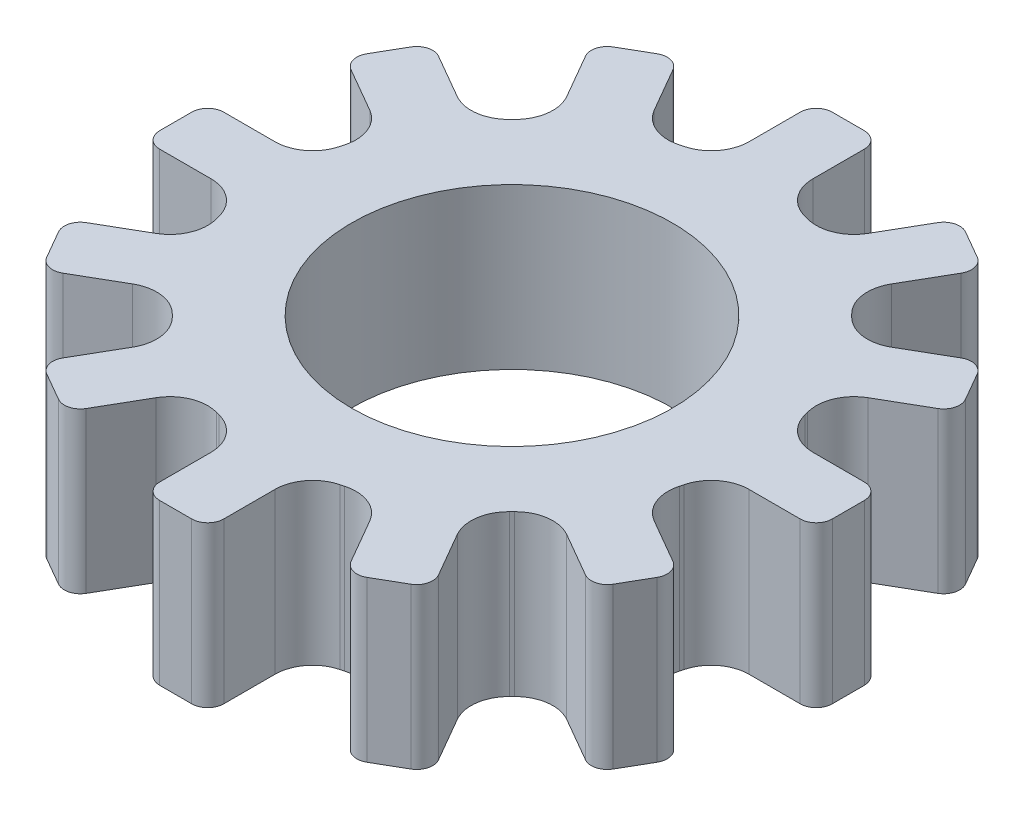
SolidWorks part; units mm, degrees
material "6061 Alloy"
ref_plane "Front Plane" through (0, 0, 0) normal (0, 0, 1) x (1, 0, 0)
ref_plane "Top Plane" through (0, 0, 0) normal (0, 1, 0) x (1, 0, 0)
ref_plane "Right Plane" through (0, 0, 0) normal (1, 0, 0) x (0, 0, -1)
sketch "Sketch1" plane through (0, 0, 0) normal (0, 1, 0) x (1, 0, 0)
  line L0 (0, 0) -> (0, 9.525) construction
  line L7 (-1.27, 10.6703) -> (-1.27, 12.7)
  line L8 (-0.635, 13.335) -> (0.635, 13.335)
  line L9 (1.27, 12.7) -> (1.27, 10.6703)
  line L10 (4.2353, 9.8757) -> (5.2501, 11.6335)
  line L11 (6.1176, 11.8659) -> (7.2174, 11.2309)
  line L12 (7.4499, 10.3635) -> (6.435, 8.6057)
  line L13 (8.6057, 6.435) -> (10.3635, 7.4499)
  line L14 (11.2309, 7.2174) -> (11.8659, 6.1176)
  line L15 (11.6335, 5.2501) -> (9.8757, 4.2353)
  line L16 (10.6703, 1.27) -> (12.7, 1.27)
  line L17 (13.335, 0.635) -> (13.335, -0.635)
  line L18 (12.7, -1.27) -> (10.6703, -1.27)
  line L19 (9.8757, -4.2353) -> (11.6335, -5.2501)
  line L20 (11.8659, -6.1176) -> (11.2309, -7.2174)
  line L21 (10.3635, -7.4499) -> (8.6057, -6.435)
  line L22 (6.435, -8.6057) -> (7.4499, -10.3635)
  line L23 (7.2174, -11.2309) -> (6.1176, -11.8659)
  line L24 (5.2501, -11.6335) -> (4.2353, -9.8757)
  line L25 (1.27, -10.6703) -> (1.27, -12.7)
  line L26 (0.635, -13.335) -> (-0.635, -13.335)
  line L27 (-1.27, -12.7) -> (-1.27, -10.6703)
  line L28 (-4.2353, -9.8757) -> (-5.2501, -11.6335)
  line L29 (-6.1176, -11.8659) -> (-7.2174, -11.2309)
  line L30 (-7.4499, -10.3635) -> (-6.435, -8.6057)
  line L31 (-8.6057, -6.435) -> (-10.3635, -7.4499)
  line L32 (-11.2309, -7.2174) -> (-11.8659, -6.1176)
  line L33 (-11.6335, -5.2501) -> (-9.8757, -4.2353)
  line L34 (-10.6703, -1.27) -> (-12.7, -1.27)
  line L35 (-13.335, -0.635) -> (-13.335, 0.635)
  line L36 (-12.7, 1.27) -> (-10.6703, 1.27)
  line L37 (-9.8757, 4.2353) -> (-11.6335, 5.2501)
  line L38 (-11.8659, 6.1176) -> (-11.2309, 7.2174)
  line L39 (-10.3635, 7.4499) -> (-8.6057, 6.435)
  line L40 (-6.435, 8.6057) -> (-7.4499, 10.3635)
  line L41 (-7.2174, 11.2309) -> (-6.1176, 11.8659)
  line L42 (-5.2501, 11.6335) -> (-4.2353, 9.8757)
  line L43 (0, 0) -> (2.3922, 9.2197) construction
  line L44 (-2.3922, 9.2197) -> (-2.5381, 9.1806)
  line L45 (2.5381, 9.1806) -> (2.3922, 9.2197)
  line L46 (6.7884, 6.6816) -> (6.6816, 6.7884)
  line L47 (9.2197, 2.3922) -> (9.1806, 2.5381)
  line L48 (9.1806, -2.5381) -> (9.2197, -2.3922)
  line L49 (6.6816, -6.7884) -> (6.7884, -6.6816)
  line L50 (2.3922, -9.2197) -> (2.5381, -9.1806)
  line L51 (-2.5381, -9.1806) -> (-2.3922, -9.2197)
  line L52 (-6.7884, -6.6816) -> (-6.6816, -6.7884)
  line L53 (-9.2197, -2.3922) -> (-9.1806, -2.5381)
  line L54 (-9.1806, 2.5381) -> (-9.2197, 2.3922)
  line L55 (-6.6816, 6.7884) -> (-6.7884, 6.6816)
  line L56 (0, 0) -> (-2.5381, 9.1806) construction
  circle A0 centre (0, 0) radius 6.3627
  circle A1 centre (0, 0) radius 9.525 construction
  arc A2 (-2.3922, 9.2197) -> (-1.27, 10.6703) centre (-2.7686, 10.6703) ccw
  arc A3 (0.635, 13.335) -> (1.27, 12.7) centre (0.635, 12.7) cw
  arc A4 (1.27, 10.6703) -> (2.3922, 9.2197) centre (2.7686, 10.6703) ccw
  arc A5 (-1.27, 12.7) -> (-0.635, 13.335) centre (-0.635, 12.7) cw
  arc A6 (2.5381, 9.1806) -> (4.2353, 9.8757) centre (2.9375, 10.625) ccw
  arc A7 (7.2174, 11.2309) -> (7.4499, 10.3635) centre (6.8999, 10.681) cw
  arc A8 (6.435, 8.6057) -> (6.6816, 6.7884) centre (7.7328, 7.8564) ccw
  arc A9 (5.2501, 11.6335) -> (6.1176, 11.8659) centre (5.8001, 11.316) cw
  arc A10 (6.7884, 6.6816) -> (8.6057, 6.435) centre (7.8564, 7.7328) ccw
  arc A11 (11.8659, 6.1176) -> (11.6335, 5.2501) centre (11.316, 5.8001) cw
  arc A12 (9.8757, 4.2353) -> (9.1806, 2.5381) centre (10.625, 2.9375) ccw
  arc A13 (10.3635, 7.4499) -> (11.2309, 7.2174) centre (10.681, 6.8999) cw
  arc A14 (9.2197, 2.3922) -> (10.6703, 1.27) centre (10.6703, 2.7686) ccw
  arc A15 (13.335, -0.635) -> (12.7, -1.27) centre (12.7, -0.635) cw
  arc A16 (10.6703, -1.27) -> (9.2197, -2.3922) centre (10.6703, -2.7686) ccw
  arc A17 (12.7, 1.27) -> (13.335, 0.635) centre (12.7, 0.635) cw
  arc A18 (9.1806, -2.5381) -> (9.8757, -4.2353) centre (10.625, -2.9375) ccw
  arc A19 (11.2309, -7.2174) -> (10.3635, -7.4499) centre (10.681, -6.8999) cw
  arc A20 (8.6057, -6.435) -> (6.7884, -6.6816) centre (7.8564, -7.7328) ccw
  arc A21 (11.6335, -5.2501) -> (11.8659, -6.1176) centre (11.316, -5.8001) cw
  arc A22 (6.6816, -6.7884) -> (6.435, -8.6057) centre (7.7328, -7.8564) ccw
  arc A23 (6.1176, -11.8659) -> (5.2501, -11.6335) centre (5.8001, -11.316) cw
  arc A24 (4.2353, -9.8757) -> (2.5381, -9.1806) centre (2.9375, -10.625) ccw
  arc A25 (7.4499, -10.3635) -> (7.2174, -11.2309) centre (6.8999, -10.681) cw
  arc A26 (2.3922, -9.2197) -> (1.27, -10.6703) centre (2.7686, -10.6703) ccw
  arc A27 (-0.635, -13.335) -> (-1.27, -12.7) centre (-0.635, -12.7) cw
  arc A28 (-1.27, -10.6703) -> (-2.3922, -9.2197) centre (-2.7686, -10.6703) ccw
  arc A29 (1.27, -12.7) -> (0.635, -13.335) centre (0.635, -12.7) cw
  arc A30 (-2.5381, -9.1806) -> (-4.2353, -9.8757) centre (-2.9375, -10.625) ccw
  arc A31 (-7.2174, -11.2309) -> (-7.4499, -10.3635) centre (-6.8999, -10.681) cw
  arc A32 (-6.435, -8.6057) -> (-6.6816, -6.7884) centre (-7.7328, -7.8564) ccw
  arc A33 (-5.2501, -11.6335) -> (-6.1176, -11.8659) centre (-5.8001, -11.316) cw
  arc A34 (-6.7884, -6.6816) -> (-8.6057, -6.435) centre (-7.8564, -7.7328) ccw
  arc A35 (-11.8659, -6.1176) -> (-11.6335, -5.2501) centre (-11.316, -5.8001) cw
  arc A36 (-9.8757, -4.2353) -> (-9.1806, -2.5381) centre (-10.625, -2.9375) ccw
  arc A37 (-10.3635, -7.4499) -> (-11.2309, -7.2174) centre (-10.681, -6.8999) cw
  arc A38 (-9.2197, -2.3922) -> (-10.6703, -1.27) centre (-10.6703, -2.7686) ccw
  arc A39 (-13.335, 0.635) -> (-12.7, 1.27) centre (-12.7, 0.635) cw
  arc A40 (-10.6703, 1.27) -> (-9.2197, 2.3922) centre (-10.6703, 2.7686) ccw
  arc A41 (-12.7, -1.27) -> (-13.335, -0.635) centre (-12.7, -0.635) cw
  arc A42 (-9.1806, 2.5381) -> (-9.8757, 4.2353) centre (-10.625, 2.9375) ccw
  arc A43 (-11.2309, 7.2174) -> (-10.3635, 7.4499) centre (-10.681, 6.8999) cw
  arc A44 (-8.6057, 6.435) -> (-6.7884, 6.6816) centre (-7.8564, 7.7328) ccw
  arc A45 (-11.6335, 5.2501) -> (-11.8659, 6.1176) centre (-11.316, 5.8001) cw
  arc A46 (-6.6816, 6.7884) -> (-6.435, 8.6057) centre (-7.7328, 7.8564) ccw
  arc A47 (-6.1176, 11.8659) -> (-5.2501, 11.6335) centre (-5.8001, 11.316) cw
  arc A48 (-4.2353, 9.8757) -> (-2.5381, 9.1806) centre (-2.9375, 10.625) ccw
  arc A49 (-7.4499, 10.3635) -> (-7.2174, 11.2309) centre (-6.8999, 10.681) cw
  point P1 (0, 13.335)
  point P26 (6.6675, 11.5484)
  point P39 (11.5484, 6.6675)
  point P52 (13.335, 0)
  point P65 (11.5484, -6.6675)
  point P78 (6.6675, -11.5484)
  point P91 (0, -13.335)
  point P104 (-6.6675, -11.5484)
  point P117 (-11.5484, -6.6675)
  point P130 (-13.335, 0)
  point P143 (-11.5484, 6.6675)
  point P156 (-6.6675, 11.5484)
  dimension "D2" = 19.05
  dimension "D3" = 1.4986
  dimension "D6" = 0.635
  dimension "D11" = 12.7254
  dimension "D4" = 2.54
  dimension "D5" = 3.81
  dimension "D8" = 9.525
  dimension "D9" = 12
  dimension "D10" = 9.525
  dimension "D7" = 12
extrude "Boss-Extrude1" add sketch "Sketch1" along normal blind 6.35 contours A49 L40 A46 L55 A44 L39 A43 L38 A45 L37 A42 L54 A40 L36 A39 L35 A41 L34 A38 L53 A36 L33 A35 L32 A37 L31 A34 L52 A32 L30 A31 L29 A33 L28 A30 L51 A28 L27 A27 L26 A29 L25 A26 L50 A24 L24 A23 L23 A25 L22 A22
